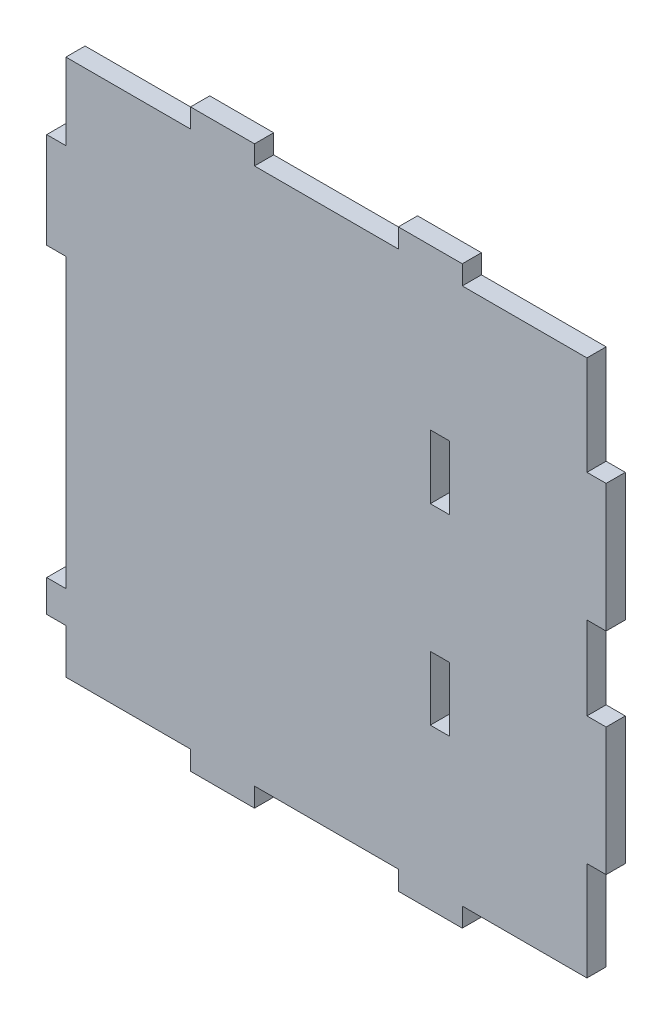
SolidWorks part; units mm, degrees
ref_plane "Plan de face" through (0, 0, 0) normal (0, 0, 1) x (1, 0, 0)
ref_plane "Plan de dessus" through (0, 0, 0) normal (0, 1, 0) x (1, 0, 0)
ref_plane "Plan de droite" through (0, 0, 0) normal (1, 0, 0) x (0, 0, -1)
sketch "Esquisse1" plane through (0, 0, 0) normal (0, 0, 1) x (1, 0, 0)
  line L1 (0, 0) -> (-175, 0)
  line L2 (0, 0) -> (0, 180)
  line L3 (0, 180) -> (-175, 180)
  line L4 (-175, 0) -> (-175, 180)
  dimension "D1" = 180
  dimension "D2" = 175
extrude "Boss.-Extru.1" add sketch "Esquisse1" along normal blind 6
sketch "Esquisse2" plane through (0, 0, 6) normal (0, 0, 1) x (1, 0, 0)
  line L0 (0, 0) -> (0, 180) construction
  line L1 (0, 180) -> (-6, 180)
  line L2 (0, 180) -> (0, 143)
  line L3 (0, 143) -> (-6, 143)
  line L4 (-6, 174) -> (-6, 143)
  line L5 (0, 103) -> (-6, 103)
  line L6 (0, 103) -> (0, 77)
  line L7 (0, 77) -> (-6, 77)
  line L8 (-6, 103) -> (-6, 77)
  line L9 (-175, 0) -> (0, 0) construction
  line L10 (0, 0) -> (-6, 0)
  line L11 (0, 0) -> (0, 37)
  line L12 (0, 37) -> (-6, 37)
  line L13 (-6, 6) -> (-6, 37)
  line L14 (-175, 0) -> (-130, 0)
  line L15 (-175, 0) -> (-175, 6)
  line L16 (-169, 6) -> (-130, 6)
  line L17 (-130, 0) -> (-130, 6)
  line L18 (-110, 0) -> (-65, 0)
  line L19 (-110, 0) -> (-110, 6)
  line L20 (-110, 6) -> (-65, 6)
  line L21 (-65, 0) -> (-65, 6)
  line L23 (-45, 0) -> (-6, 0)
  line L24 (-45, 0) -> (-45, 6)
  line L25 (-45, 6) -> (-6, 6)
  line L26 (-175, 180) -> (-175, 0) construction
  line L28 (-175, 174) -> (-175, 150)
  line L29 (-175, 150) -> (-169, 150)
  line L30 (-169, 174) -> (-169, 150)
  line L31 (0, 180) -> (-175, 180) construction
  line L32 (-175, 120) -> (-169, 120)
  line L33 (-175, 120) -> (-175, 30)
  line L34 (-175, 30) -> (-169, 30)
  line L35 (-169, 120) -> (-169, 30)
  line L37 (-175, 180) -> (-130, 180)
  line L38 (-175, 180) -> (-175, 174)
  line L39 (-169, 174) -> (-130, 174)
  line L40 (-130, 180) -> (-130, 174)
  line L41 (-110, 180) -> (-65, 180)
  line L42 (-110, 180) -> (-110, 174)
  line L43 (-110, 174) -> (-65, 174)
  line L44 (-65, 180) -> (-65, 174)
  line L45 (-45, 180) -> (-6, 180)
  line L46 (-45, 180) -> (-45, 174)
  line L47 (-45, 174) -> (-6, 174)
  line L48 (-175, 20) -> (-169, 20)
  line L49 (-175, 20) -> (-175, 6)
  line L51 (-169, 20) -> (-169, 6)
  dimension "D1" = 6
  dimension "D2" = 6
  dimension "D3" = 6
  dimension "D4" = 26
  dimension "D5" = 37
  dimension "D6" = 40
  dimension "D7" = 37
  dimension "D8" = 45
  dimension "D9" = 6
  dimension "D10" = 6
  dimension "D11" = 20
  dimension "D12" = 45
  dimension "D13" = 6
  dimension "D14" = 20
  dimension "D15" = 14
  dimension "D16" = 10
  dimension "D17" = 24
  dimension "D18" = 30
  dimension "D19" = 6
  dimension "D20" = 6
  dimension "D21" = 45
  dimension "D22" = 6
  dimension "D23" = 6
  dimension "D24" = 45
  dimension "D25" = 20
  dimension "D26" = 20
  dimension "D27" = 6
  dimension "D28" = 6
extrude "Enlèv. mat encoche " cut sketch "Esquisse2" against normal through all
sketch "Esquisse3" plane through (0, 0, 6) normal (0, 0, 1) x (1, 0, 0)
  line L1 (-55, 130) -> (-49, 130)
  line L2 (-55, 130) -> (-55, 110)
  line L3 (-55, 110) -> (-49, 110)
  line L4 (-49, 130) -> (-49, 110)
  line L5 (-55, 70) -> (-49, 70)
  line L6 (-55, 70) -> (-55, 50)
  line L7 (-55, 50) -> (-49, 50)
  line L8 (-49, 70) -> (-49, 50)
  line L9 (0, 103) -> (0, 143) construction
  line L10 (0, 37) -> (0, 77) construction
  line L11 (-45, 180) -> (-65, 180) construction
  dimension "D1" = 20
  dimension "D2" = 20
  dimension "D3" = 40
  dimension "D4" = 49
  dimension "D5" = 6
  dimension "D6" = 6
  dimension "D7" = 49
  dimension "D8" = 50
extrude "Enlèv. mat encoche étage" cut sketch "Esquisse3" against normal blind 6
